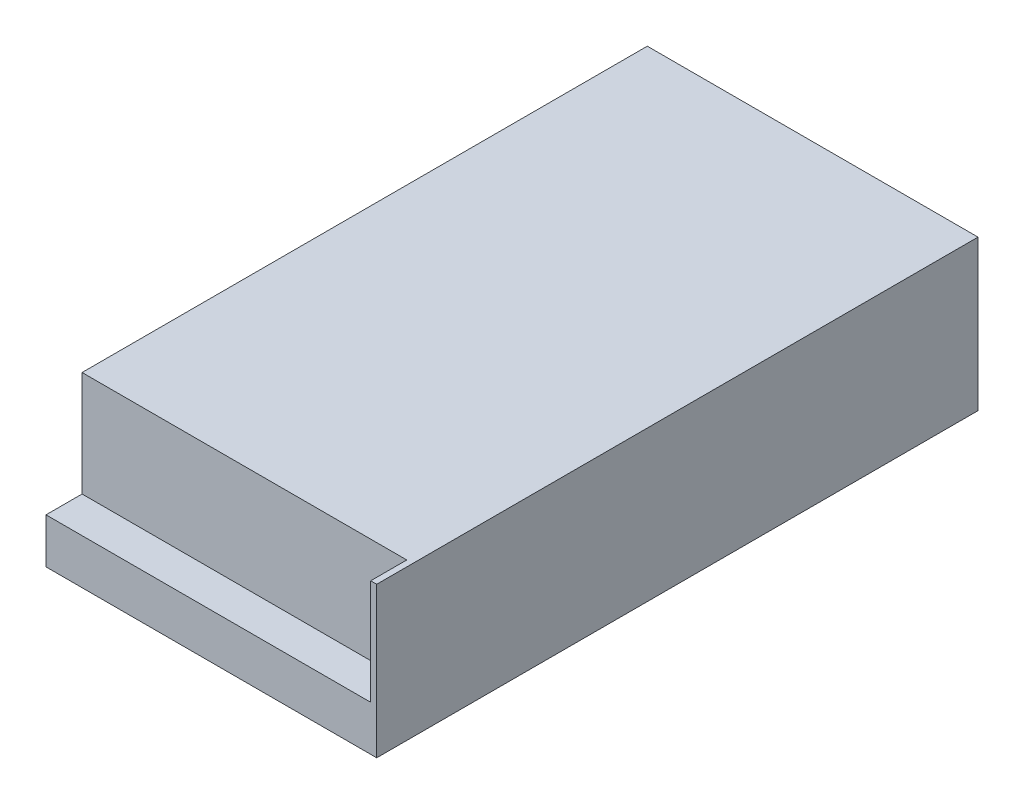
SolidWorks part; units mm, degrees
material "6061 Alloy"
ref_plane "Front Plane" through (0, 0, 0) normal (0, 0, 1) x (1, 0, 0)
ref_plane "Top Plane" through (0, 0, 0) normal (0, 1, 0) x (1, 0, 0)
ref_plane "Right Plane" through (0, 0, 0) normal (1, 0, 0) x (0, 0, -1)
sketch "Sketch1" plane through (0, 0, 0) normal (0, 1, 0) x (1, 0, 0)
  line L1 (-55, -100) -> (55, -100)
  line L2 (-55, -100) -> (-55, 100)
  line L3 (-55, 100) -> (55, 100)
  line L4 (55, -100) -> (55, 100)
  line L5 (-55, -100) -> (55, 100) construction
  line L6 (-55, 100) -> (55, -100) construction
  point P0 (0, 0)
  dimension "D1" = 200
  dimension "D2" = 110
extrude "Boss-Extrude1" add sketch "Sketch1" along normal blind 50
sketch "Sketch2" plane through (0, 50, 0) normal (0, 1, 0) x (1, 0, 0)
  line L0 (55, -100) -> (55, 100) construction
  line L1 (-55, -100) -> (53, -100)
  line L2 (-55, -100) -> (-55, -88)
  line L3 (-55, -88) -> (53, -88)
  line L4 (53, -100) -> (53, -88)
  dimension "D1" = 2
  dimension "D2" = 12
extrude "Cut-Extrude1" cut sketch "Sketch2" against normal blind 35
